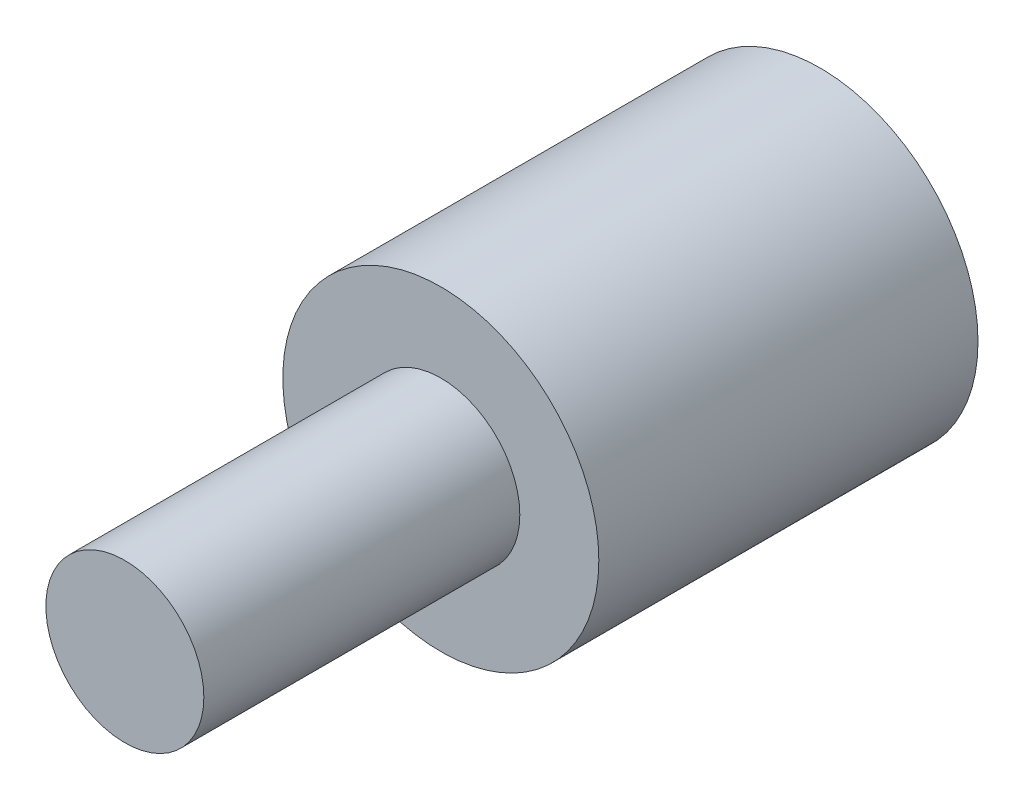
SolidWorks part; units mm, degrees
ref_plane "Front Plane" through (0, 0, 0) normal (0, 0, 1) x (1, 0, 0)
ref_plane "Top Plane" through (0, 0, 0) normal (0, 1, 0) x (1, 0, 0)
ref_plane "Right Plane" through (0, 0, 0) normal (1, 0, 0) x (0, 0, -1)
sketch "Sketch1" plane through (0, 0, 0) normal (0, 0, 1) x (1, 0, 0)
  circle A0 centre (0, 0) radius 25
  dimension "D1" = 50
extrude "Boss-Extrude1" add sketch "Sketch1" against normal blind 60
sketch "Sketch2" plane through (0, 0, 0) normal (0, 0, 1) x (1, 0, 0)
  circle A0 centre (0, 0) radius 12.5
  dimension "D1" = 25
extrude "Boss-Extrude2" add sketch "Sketch2" along normal blind 50
ref_plane "Plane1" through (125, 0, 0) normal (1, 0, 0) x (0, 0, -1)
